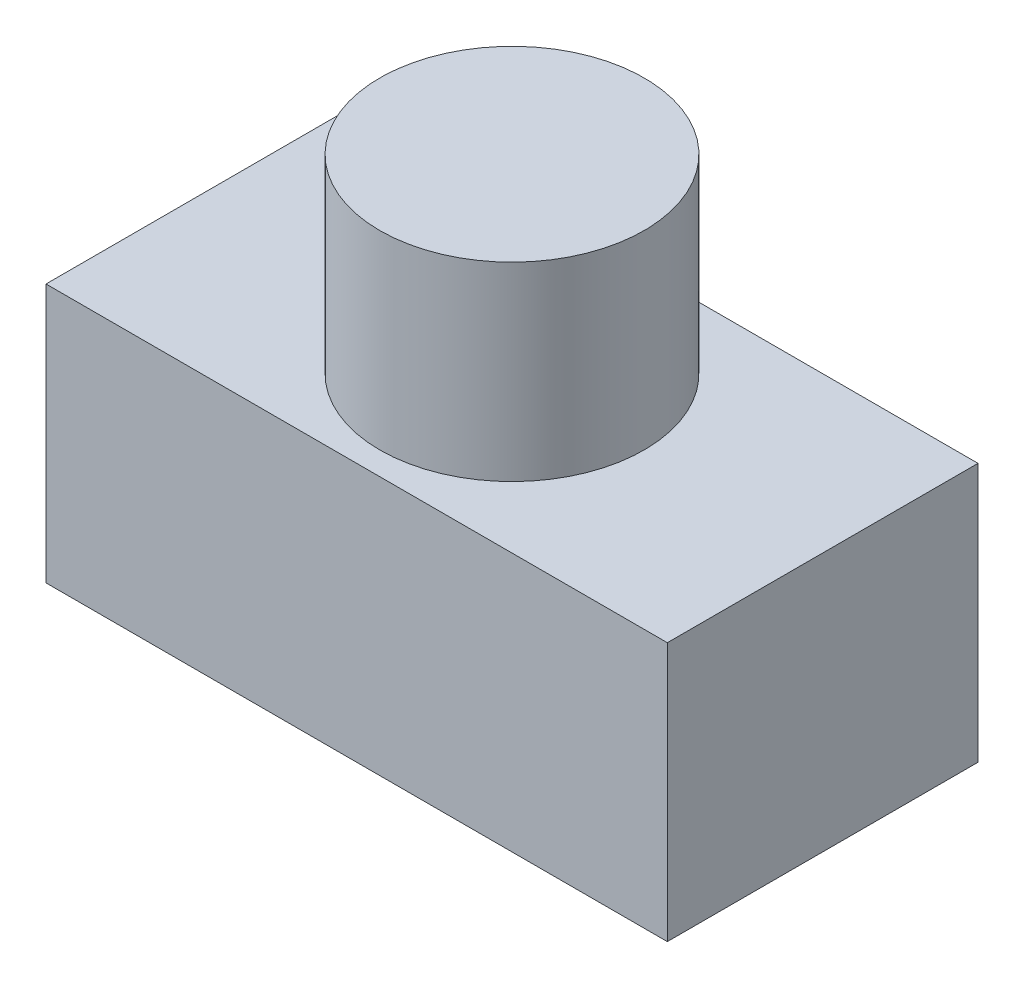
SolidWorks part; units mm, degrees
ref_plane "Front Plane" through (0, 0, 0) normal (0, 0, 1) x (1, 0, 0)
ref_plane "Top Plane" through (0, 0, 0) normal (0, 1, 0) x (1, 0, 0)
ref_plane "Right Plane" through (0, 0, 0) normal (1, 0, 0) x (0, 0, -1)
sketch "Sketch1" plane through (0, 0, 0) normal (0, 0, 1) x (1, 0, 0)
  line L1 (-152.4, -63.5) -> (152.4, -63.5)
  line L2 (-152.4, -63.5) -> (-152.4, 63.5)
  line L3 (-152.4, 63.5) -> (152.4, 63.5)
  line L4 (152.4, -63.5) -> (152.4, 63.5)
  line L5 (-152.4, -63.5) -> (152.4, 63.5) construction
  line L6 (-152.4, 63.5) -> (152.4, -63.5) construction
  point P0 (0, 0)
  dimension "D1" = 304.8
  dimension "D2" = 127
extrude "Boss-Extrude1" add sketch "Sketch1" along normal mid plane 152.4
sketch "Sketch2" plane through (0, 0, 76.2) normal (0, 0, 1) x (1, 0, 0)
  line L1 (0, 50.5506) -> (-43.7781, -25.2753)
  line L2 (-43.7781, -25.2753) -> (43.7781, -25.2753)
  line L3 (43.7781, -25.2753) -> (0, 50.5506)
  circle A0 centre (0, 0) radius 25.2753 construction
extrude "Cut-Extrude1" [suppressed] cut sketch "Sketch2" against normal through all
sketch "Sketch3" plane through (152.4, 0, 0) normal (1, 0, 0) x (0, 0, -1)
  line L1 (-61.8845, -51.332) -> (61.8845, -51.332)
  line L2 (-61.8845, -51.332) -> (-61.8845, 51.332)
  line L3 (-61.8845, 51.332) -> (61.8845, 51.332)
  line L4 (61.8845, -51.332) -> (61.8845, 51.332)
  line L5 (-61.8845, -51.332) -> (61.8845, 51.332) construction
  line L6 (-61.8845, 51.332) -> (61.8845, -51.332) construction
  point P0 (0, 0)
extrude "Cut-Extrude2" [suppressed] cut sketch "Sketch3" against normal through all
sketch "Sketch4" plane through (0, 63.5, 0) normal (0, 1, 0) x (1, 0, 0)
  circle A0 centre (0, 0) radius 46.9609
extrude "Cut-Extrude3" cut sketch "Sketch4" against normal through all
sketch "Sketch5" plane through (0, 63.5, 0) normal (0, 1, 0) x (1, 0, 0)
  circle A0 centre (0, 0) radius 64.855
extrude "Boss-Extrude2" add sketch "Sketch5" along normal blind 93.218
